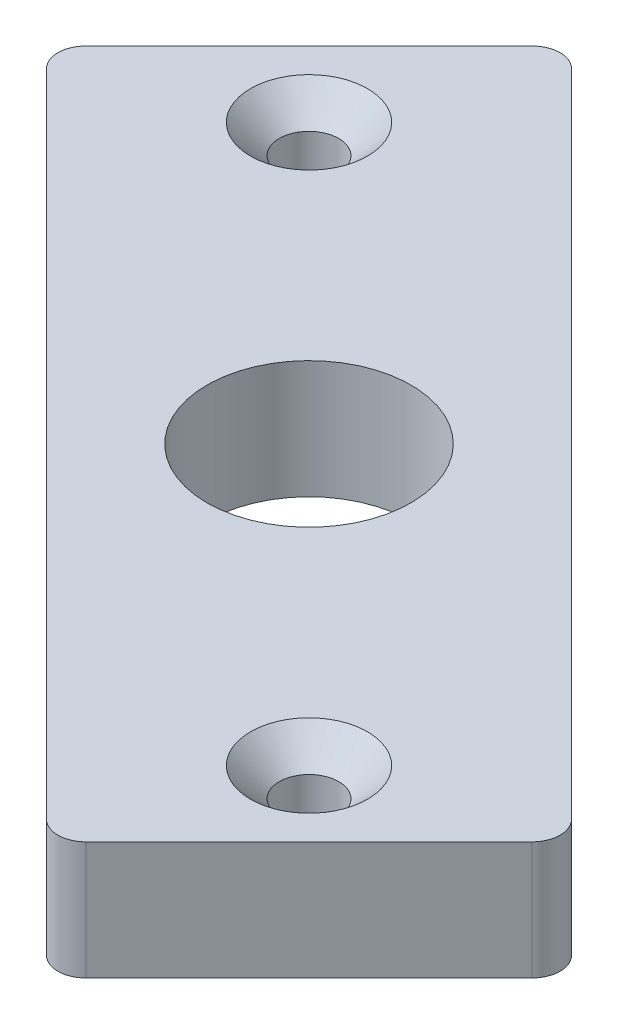
SolidWorks part; units mm, degrees
material "6061 Alloy"
ref_plane "Front Plane" through (0, 0, 0) normal (0, 0, 1) x (1, 0, 0)
ref_plane "Top Plane" through (0, 0, 0) normal (0, 1, 0) x (1, 0, 0)
ref_plane "Right Plane" through (0, 0, 0) normal (1, 0, 0) x (0, 0, -1)
sketch "Sketch2" plane through (0, 0, 0) normal (0, 1, 0) x (1, 0, 0)
  line L0 (-51.2652, 22.981) -> (22.981, -51.2652)
  line L1 (-42.5, 42.5) -> (42.5, 42.5) construction
  line L2 (-42.5, 42.5) -> (-42.5, -42.5) construction
  line L3 (-42.5, -42.5) -> (42.5, -42.5) construction
  line L4 (42.5, 42.5) -> (42.5, -42.5) construction
  line L5 (-30, 30) -> (30, 30) construction
  line L6 (-30, 30) -> (-30, -30) construction
  line L7 (-30, -30) -> (30, -30) construction
  line L8 (30, 30) -> (30, -30) construction
  line L9 (-51.2652, 22.981) -> (-22.981, 51.2652)
  line L10 (22.981, -51.2652) -> (51.2652, -22.981)
  line L11 (-22.981, 51.2652) -> (51.2652, -22.981)
  line L12 (-51.2652, 22.981) -> (51.2652, -22.981) construction
  line L13 (22.981, -51.2652) -> (-22.981, 51.2652) construction
  line L14 (-37.1231, 37.1231) -> (37.1231, -37.1231) construction
  circle A0 centre (0, 0) radius 10.993
  circle A1 centre (-30, 30) radius 2.5 construction
  circle A2 centre (30, 30) radius 2.5 construction
  circle A3 centre (30, -30) radius 2.5 construction
  circle A4 centre (-30, -30) radius 2.5 construction
  point P4 (0, 42.5)
  point P6 (-42.5, 0)
  point P13 (0, 30)
  point P14 (-30, 0)
  dimension "D1" = 21.986
  dimension "D3" = 5
  dimension "D2" = 85
  dimension "D4" = 60
  dimension "D5" = 40
  dimension "D6" = 105
extrude "Boss-Extrude1" add sketch "Sketch2" against normal blind 12.7 contours L2 L3 L4 L1
hole_wizard "CSK for M6 Flat Head Machine Screw1" positions "3DSketch1" profile "Sketch3" countersink size "M6" standard "ANSI Metric" end condition through all
sketch3d "3DSketch1"
  point P31 (-30, 0, -30)
  point P33 (30, 0, 30)
  point P36 (-30, 0, -30)
  point P38 (30, 0, 30)
sketch "Sketch3" plane through (-30, 0, -30) normal (1, 0, 0) x (0, 0, 1)
  line L0 (0, 0) -> (0, 12.7)
  line L1 (0, 12.7) -> (3.2, 12.7)
  line L2 (3.2, 12.7) -> (3.2, 3.1)
  line L3 (3.2, 3.1) -> (6.3, 0)
  line L5 (6.3, 0) -> (0, 0)
  line L6 (-3.2, 3.1) -> (-6.3, 0) construction
  line L11 (0, -6.35) -> (0, 107.95) construction
  dimension "Thru Hole Dia." = 6.4
  dimension "Thru Hole Depth" = 12.7
  dimension "Near C'Sink Dia." = 12.6
  dimension "Near C'Sink Angle" = 90
fillet "Fillet1" radius 3 4 edges at (22.981, -6.35, 51.2652) (51.2652, -6.35, 22.981) (-22.981, -6.35, -51.2652) (-51.2652, -6.35, -22.981)
